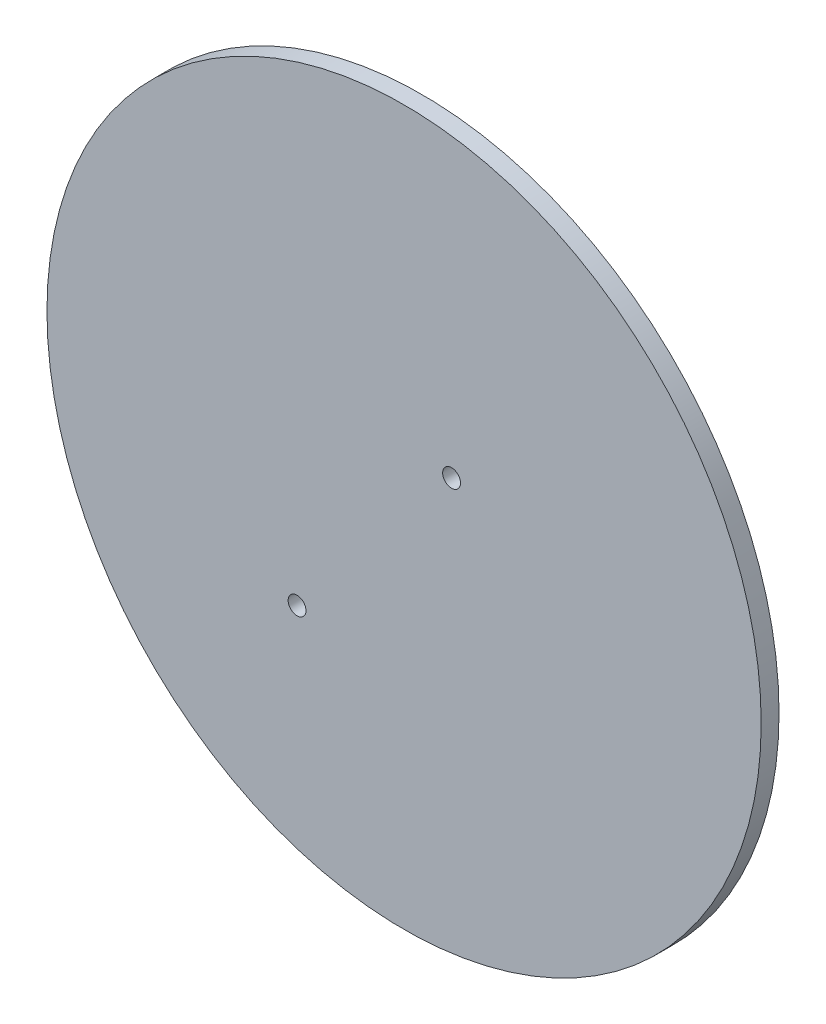
SolidWorks part; units mm, degrees
ref_plane "Front Plane" through (0, 0, 0) normal (0, 0, 1) x (1, 0, 0)
ref_plane "Top Plane" through (0, 0, 0) normal (0, 1, 0) x (1, 0, 0)
ref_plane "Right Plane" through (0, 0, 0) normal (1, 0, 0) x (0, 0, -1)
sketch "Sketch1" plane through (0, 0, 0) normal (0, 0, 1) x (1, 0, 0)
  circle A0 centre (0, 0) radius 40.0242
  circle A1 centre (5.3221, 6.4666) radius 1
  circle A2 centre (-11.9945, -14.5739) radius 1
extrude "Boss-Extrude1" add sketch "Sketch1" along normal blind 2
